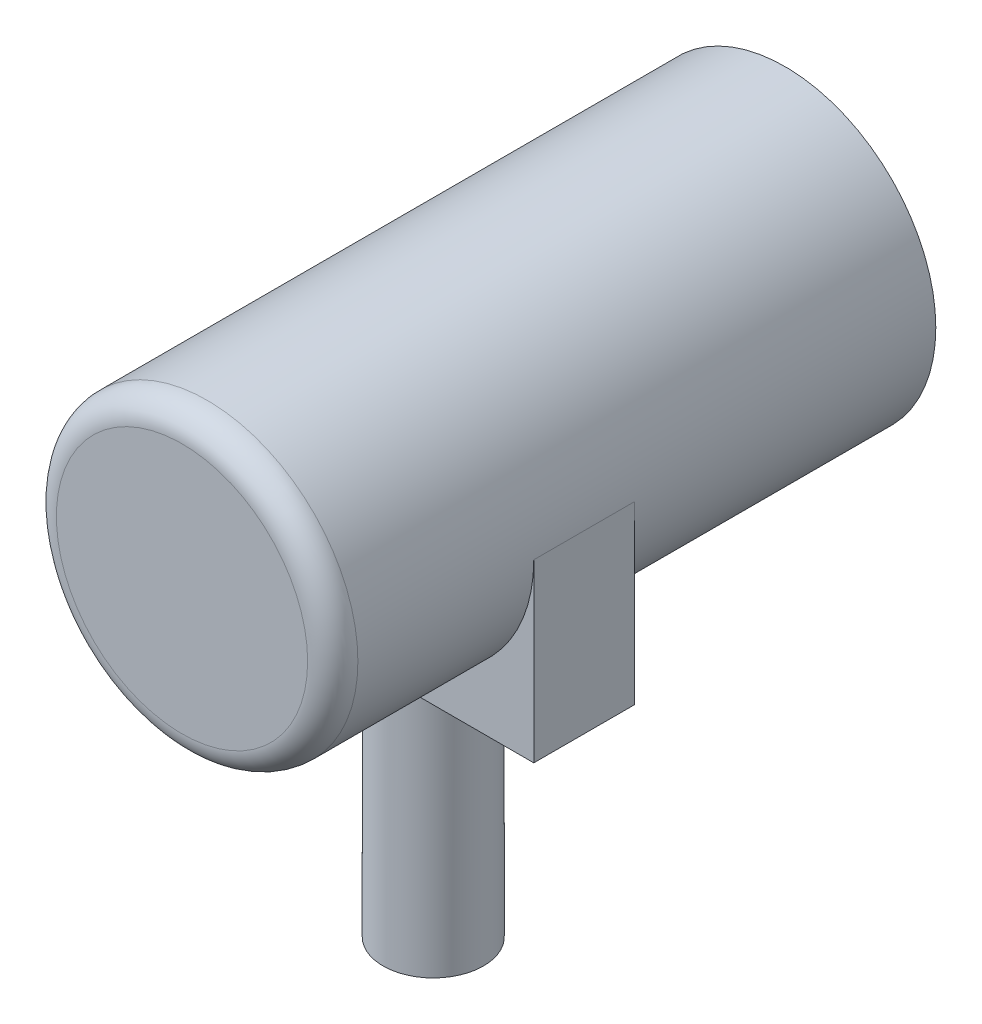
SolidWorks part; units mm, degrees
ref_plane "Front Plane" through (0, 0, 0) normal (0, 0, 1) x (1, 0, 0)
ref_plane "Top Plane" through (0, 0, 0) normal (0, 1, 0) x (1, 0, 0)
ref_plane "Right Plane" through (0, 0, 0) normal (1, 0, 0) x (0, 0, -1)
sketch "Tube Sketch" plane through (0, 0, 0) normal (0, 0, 1) x (1, 0, 0)
  circle A0 centre (0, 0) radius 30
  dimension "D1" = 60
extrude "Tube Extrude" add sketch "Tube Sketch" against normal blind 120
shell "Tube Shell" thickness 5
ref_plane "Mid Plane" through (0, 0, -60) normal (0, 0, 1) x (1, 0, 0)
sketch "Support Band Sketch" plane through (0, 0, -60) normal (0, 0, 1) x (1, 0, 0)
  line L0 (-30, 0) -> (-30, -35)
  line L1 (-30, -35) -> (30, -35)
  line L2 (30, -35) -> (30, 0)
  line L3 (0, 0) -> (30, 0) construction
  line L4 (0, 0) -> (0, -35) construction
  line L5 (0, 0) -> (-30, 0) construction
  line L6 (30, -30) -> (-30, -30) construction
  arc A2 (-30, 0) -> (30, 0) centre (0, 0) ccw
  circle A3 centre (0, 0) radius 30 construction
  dimension "D1" = 5
extrude "Supprt Band Extrude" add sketch "Support Band Sketch" along normal blind 20
sketch "Pin Sketch" plane through (0, -35, 0) normal (0, -1, 0) x (1, 0, 0)
  line L0 (30, -40) -> (30, -60) construction
  line L1 (30, -50) -> (-30, -50) construction
  line L3 (-30, -40) -> (-30, -60) construction
  circle A0 centre (0, -50) radius 10
  dimension "D1" = 20
extrude "Pin Extrude" add sketch "Pin Sketch" along normal blind 50
sketch "Aperture Sketch" plane through (0, 0, -120) normal (0, 0, -1) x (-1, 0, 0)
  circle A0 centre (0, 0) radius 25
  circle A1 centre (0, 0) radius 25 construction
extrude "Aperture Extrude" add sketch "Aperture Sketch" against normal blind 2 from offset 2 offset against normal yes
fillet "Rear Fillet" radius 5 1 edges at (30, 0, 0)
